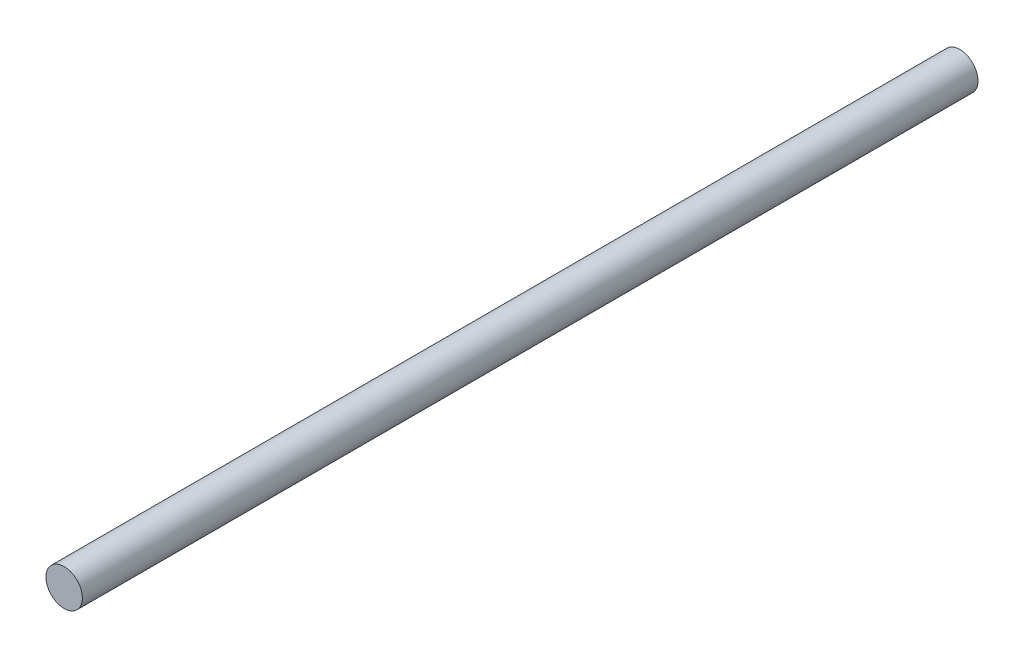
SolidWorks part; units mm, degrees
ref_plane "前视基准面" through (0, 0, 0) normal (0, 0, 1) x (1, 0, 0)
ref_plane "上视基准面" through (0, 0, 0) normal (0, 1, 0) x (1, 0, 0)
ref_plane "右视基准面" through (0, 0, 0) normal (1, 0, 0) x (0, 0, -1)
other "Configuration Table"
sketch "草图1" plane through (0, 0, 0) normal (0, 0, 1) x (1, 0, 0)
  circle A0 centre (0, 0) radius 3.8
  dimension "diameter" = 7.6
extrude "Cable" add sketch "草图1" along normal blind 187
